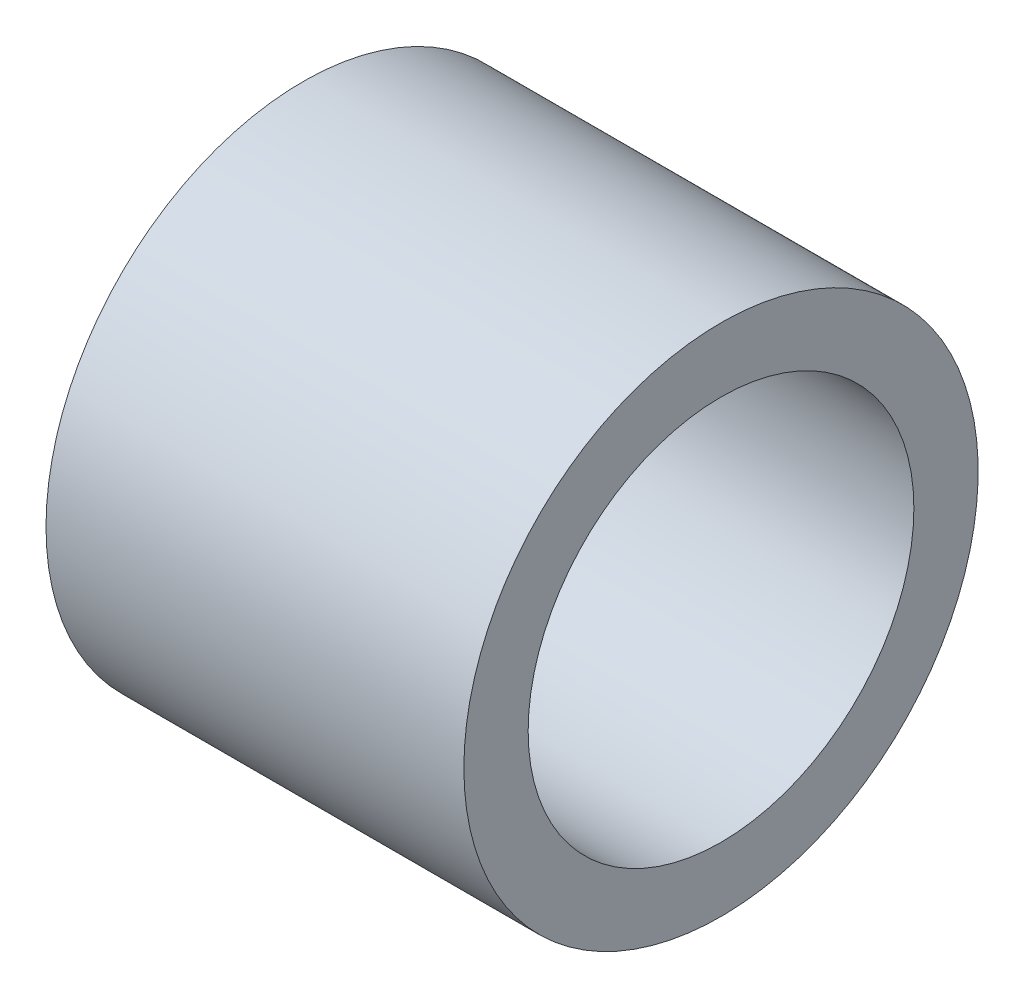
SolidWorks part; units mm, degrees
material "MCナイロン"
ref_plane "Front Plane" through (0, 0, 0) normal (0, 0, 1) x (1, 0, 0)
ref_plane "Top Plane" through (0, 0, 0) normal (0, 1, 0) x (1, 0, 0)
ref_plane "Right Plane" through (0, 0, 0) normal (1, 0, 0) x (0, 0, -1)
sketch "Sketch1" plane through (0, 0, 0) normal (0, 0, 1) x (1, 0, 0)
  line L0 (0, 0) -> (6.5, 0) construction
  line L1 (0, 3) -> (6.5, 3)
  line L2 (0, -3) -> (6.5, -3) construction
  line L3 (0, 3) -> (0, 4)
  line L4 (0, 4) -> (6.5, 4)
  line L5 (6.5, 3) -> (6.5, 4)
  dimension "D" = 8
  dimension "V" = 6
  dimension "T" = 6.5
revolve "Revolve1" add sketch "Sketch1" angle 360 about L0
